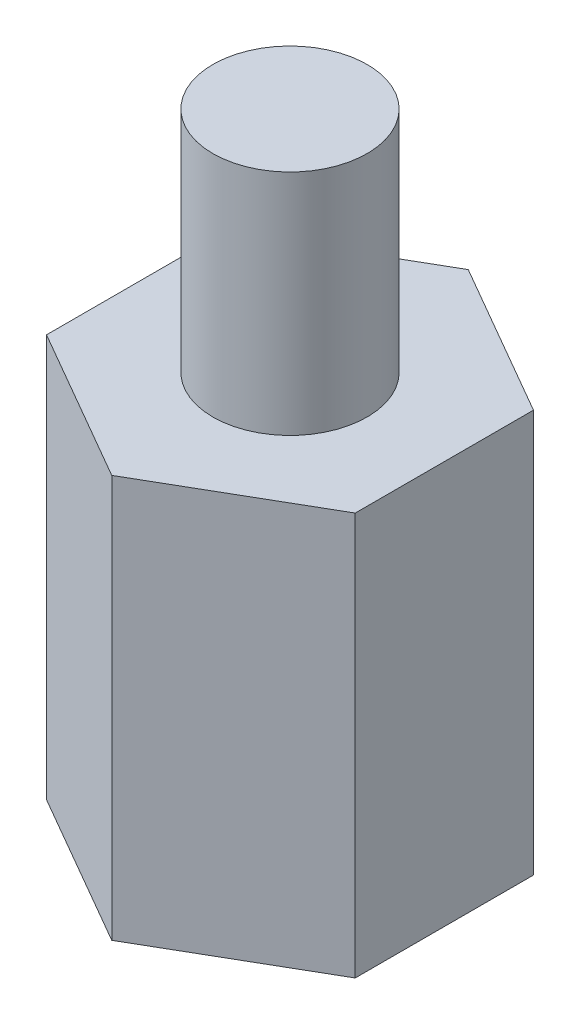
SolidWorks part; units mm, degrees
ref_plane "Спереди" through (0, 0, 0) normal (0, 0, 1) x (1, 0, 0)
ref_plane "Сверху" through (0, 0, 0) normal (0, 1, 0) x (1, 0, 0)
ref_plane "Справа" through (0, 0, 0) normal (1, 0, 0) x (0, 0, -1)
sketch "Эскиз1" plane through (0, 0, 0) normal (0, 1, 0) x (1, 0, 0)
  line L1 (0, 2.6558) -> (-2.3, 1.3279)
  line L2 (-2.3, 1.3279) -> (-2.3, -1.3279)
  line L3 (-2.3, -1.3279) -> (0, -2.6558)
  line L4 (0, -2.6558) -> (2.3, -1.3279)
  line L5 (2.3, -1.3279) -> (2.3, 1.3279)
  line L6 (2.3, 1.3279) -> (0, 2.6558)
  circle A0 centre (0, 0) radius 2.3 construction
  dimension "D1" = 4.6
extrude "Бобышка-Вытянуть1" add sketch "Эскиз1" along normal blind 6
sketch "Эскиз2" plane through (0, 6, 0) normal (0, 1, 0) x (1, 0, 0)
  circle A0 centre (0, 0) radius 1.15
  dimension "D1" = 2.3
extrude "Бобышка-Вытянуть2" add sketch "Эскиз2" along normal blind 3.4
sketch "Эскиз3" plane through (0, 0, 0) normal (0, -1, 0) x (1, 0, 0)
  circle A0 centre (0, 0) radius 1.35
  dimension "D1" = 2.7
extrude "Вырез-Вытянуть1" cut sketch "Эскиз3" against normal blind 4
